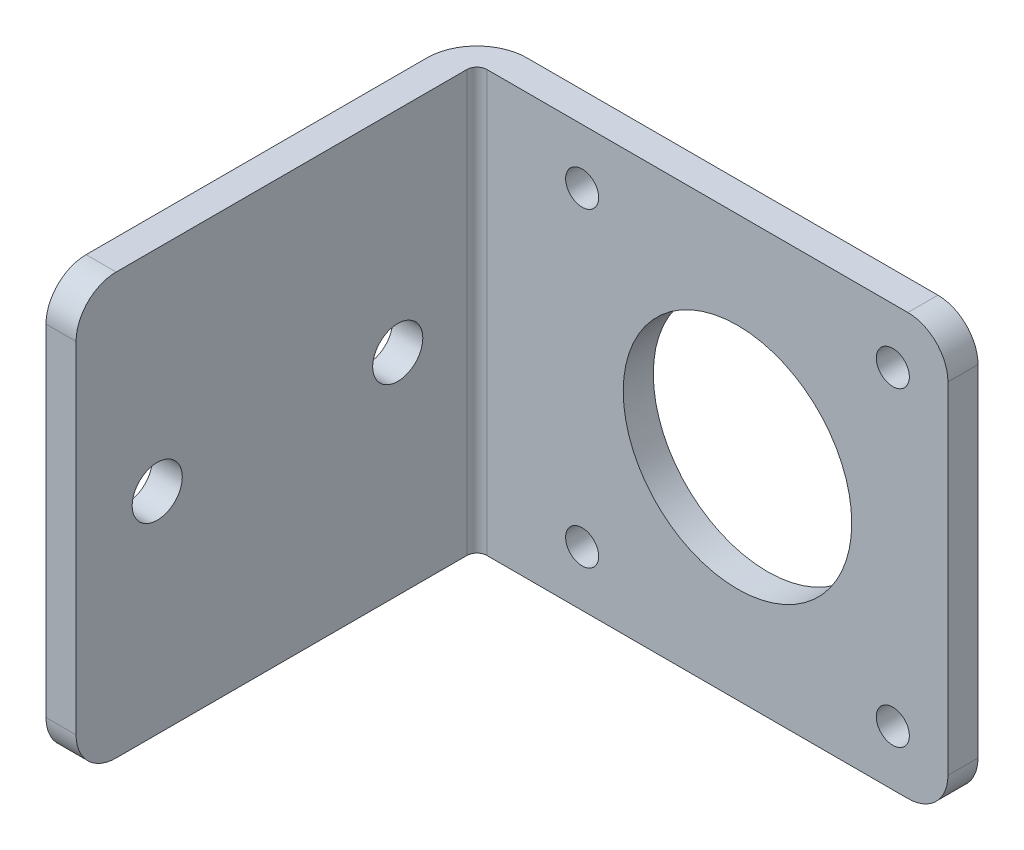
SolidWorks part; units mm, degrees
ref_plane "Front Plane" through (0, 0, 0) normal (0, 0, 1) x (1, 0, 0)
ref_plane "Top Plane" through (0, 0, 0) normal (0, 1, 0) x (1, 0, 0)
ref_plane "Right Plane" through (0, 0, 0) normal (1, 0, 0) x (0, 0, -1)
sketch "Sketch1" plane through (0, 0, 0) normal (0, 1, 0) x (1, 0, 0)
  line L0 (0, -43) -> (0, 0)
  line L1 (0, 0) -> (50, 0)
  dimension "D1" = 43
  dimension "D2" = 50
extrude "Extrude-Thin1" add sketch "Sketch1" along normal mid plane 42 thin
sketch "Sketch2" plane through (0, 0, 3) normal (0, 0, 1) x (1, 0, 0)
  line L0 (50, 0) -> (29, 0) construction
  line L1 (50, 21) -> (50, -21) construction
  line L3 (44.5, 15.5) -> (13.5, 15.5) construction
  line L4 (44.5, 15.5) -> (44.5, -15.5) construction
  line L5 (44.5, -15.5) -> (13.5, -15.5) construction
  line L6 (13.5, 15.5) -> (13.5, -15.5) construction
  line L7 (44.5, 15.5) -> (13.5, -15.5) construction
  line L8 (44.5, -15.5) -> (13.5, 15.5) construction
  circle A0 centre (29, 0) radius 11.4
  circle A1 centre (13.5, 15.5) radius 1.65
  circle A2 centre (44.5, 15.5) radius 1.65
  circle A3 centre (13.5, -15.5) radius 1.65
  circle A4 centre (44.5, -15.5) radius 1.65
  dimension "D1" = 22.8
  dimension "D2" = 21
  dimension "D5" = 3.3
  dimension "D3" = 31
  dimension "D4" = 31
extrude "Cut-Extrude1" cut sketch "Sketch2" against normal through all
sketch "Sketch3" plane through (3, 0, 0) normal (1, 0, 0) x (0, 0, -1)
  line L0 (-43, 0) -> (-34.9, 0) construction
  line L1 (-43, 21) -> (-43, -21) construction
  line L2 (-34.9, 0) -> (-10.9, 0) construction
  circle A0 centre (-34.9, 0) radius 2.5
  circle A1 centre (-10.9, 0) radius 2.5
  dimension "D1" = 5
  dimension "D2" = 24
  dimension "D3" = 5.6
extrude "Cut-Extrude2" cut sketch "Sketch3" against normal through all
fillet "Fillet1" radius 4 4 edges at (50, -21, 1.5) (50, 21, 1.5) (1.5, -21, 43) (1.5, 21, 43)
fillet "Fillet2" radius 5 1 edges at (0, 0, 0)
fillet "Fillet3" radius 1 1 edges at (3, 0, 3)
